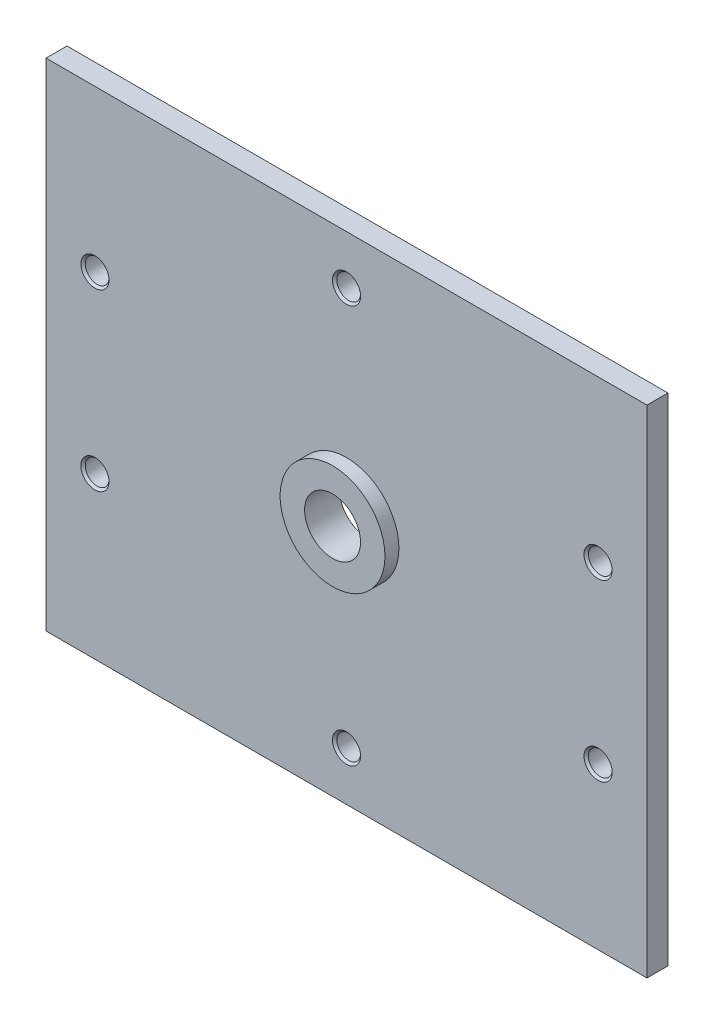
SolidWorks part; units mm, degrees
ref_plane "前视基准面" through (0, 0, 0) normal (0, 0, 1) x (1, 0, 0)
ref_plane "上视基准面" through (0, 0, 0) normal (0, 1, 0) x (1, 0, 0)
ref_plane "右视基准面" through (0, 0, 0) normal (1, 0, 0) x (0, 0, -1)
other "Configuration Table"
sketch "草图1" plane through (0, 0, 0) normal (0, 0, 1) x (1, 0, 0)
  line L1 (0, 0) -> (172, 0)
  line L2 (0, 0) -> (0, -142)
  line L3 (0, -142) -> (172, -142)
  line L4 (172, 0) -> (172, -142)
  dimension "D1" = 142
  dimension "D2" = 172
extrude "凸台-拉伸1" add sketch "草图1" along normal blind 6
sketch "草图2" plane through (0, 0, 6) normal (0, 0, 1) x (1, 0, 0)
  line L0 (0, -71) -> (172, -71)
  line L1 (0, 0) -> (0, -142) construction
  line L2 (172, -142) -> (172, 0) construction
  line L3 (0, -142) -> (172, -142) construction
  line L4 (14, -14) -> (158, -14)
  line L5 (14, -14) -> (14, -128)
  line L6 (14, -128) -> (158, -128)
  line L7 (158, -14) -> (158, -128)
  line L8 (172, 0) -> (0, 0) construction
  line L9 (86, -14) -> (86, -128)
  line L10 (48.5, -14) -> (48.5, -128)
  line L11 (123.5, -14) -> (123.5, -128)
  line L12 (14, -46) -> (158, -46)
  line L13 (14, -96) -> (158, -96)
  dimension "D1" = 14
  dimension "D2" = 14
  dimension "D3" = 14
  dimension "D4" = 14
  dimension "D5" = 75
  dimension "D6" = 37.5
  dimension "D7" = 50
  dimension "D8" = 25
hole_wizard "M8 螺纹孔1" positions "草图9" profile "草图10" tap size "M8" standard "GB"
sketch "草图9" plane through (0, 0, 6) normal (0, 0, 1) x (1, 0, 0)
  point P0 (14, -46)
  point P3 (14, -96)
  point P6 (86, -14)
  point P9 (86, -128)
  point P12 (158, -96)
  point P15 (158, -46)
sketch "草图10" plane through (14, -46, 6) normal (1, 0, 0) x (0, -1, 0)
  line L0 (0, 0) -> (0, 8.0429)
  line L1 (0, 8.0429) -> (3.4, 6)
  line L2 (3.4, 6) -> (3.4, 0.625)
  line L3 (3.4, 0.625) -> (4.025, 0)
  line L5 (4.025, 0) -> (0, 0)
  line L6 (-3.4, 0.625) -> (-4.025, 0) construction
  line L10 (0, 8.0429) -> (-3.4, 6) construction
  line L11 (0, -6.35) -> (0, 107.95) construction
  dimension "螺纹孔钻头直径" = 6.8
  dimension "螺纹孔钻头深度" = 6
  dimension "近端锥形沉头孔直径" = 8.05
  dimension "近端锥形沉头孔角度" = 90
  dimension "导头角度" = 118
cosmetic thread "孔螺蚊线1" parameters "D1"=20, "D2"=8
cosmetic thread "孔螺蚊线2" parameters "D1"=20, "D2"=8
cosmetic thread "孔螺蚊线3" parameters "D1"=20, "D2"=8
cosmetic thread "孔螺蚊线4" parameters "D1"=20, "D2"=8
cosmetic thread "孔螺蚊线5" parameters "D1"=20, "D2"=8
cosmetic thread "孔螺蚊线6" parameters "D1"=20, "D2"=8
sketch "草图11" plane through (0, 0, 6) normal (0, 0, 1) x (1, 0, 0)
  line L0 (172, 0) -> (0, 0) construction
  line L1 (0, 0) -> (0, -142) construction
  line L2 (172, 0) -> (0, 0)
  line L3 (0, 0) -> (0, -142)
  circle A0 centre (86, -71) radius 15
  point P6 (86, 0)
  point P7 (0, -71)
  dimension "D1" = 30
extrude "凸台-拉伸3" add sketch "草图11" along normal blind 4 contours A0
sketch "草图12" plane through (0, 0, 10) normal (0, 0, 1) x (1, 0, 0)
  circle A0 centre (86, -71) radius 15 construction
  circle A1 centre (86, -71) radius 15
  circle A2 centre (86, -71) radius 8
  dimension "D1" = 16
extrude "切除-拉伸1" cut sketch "草图12" against normal through all contours A2
